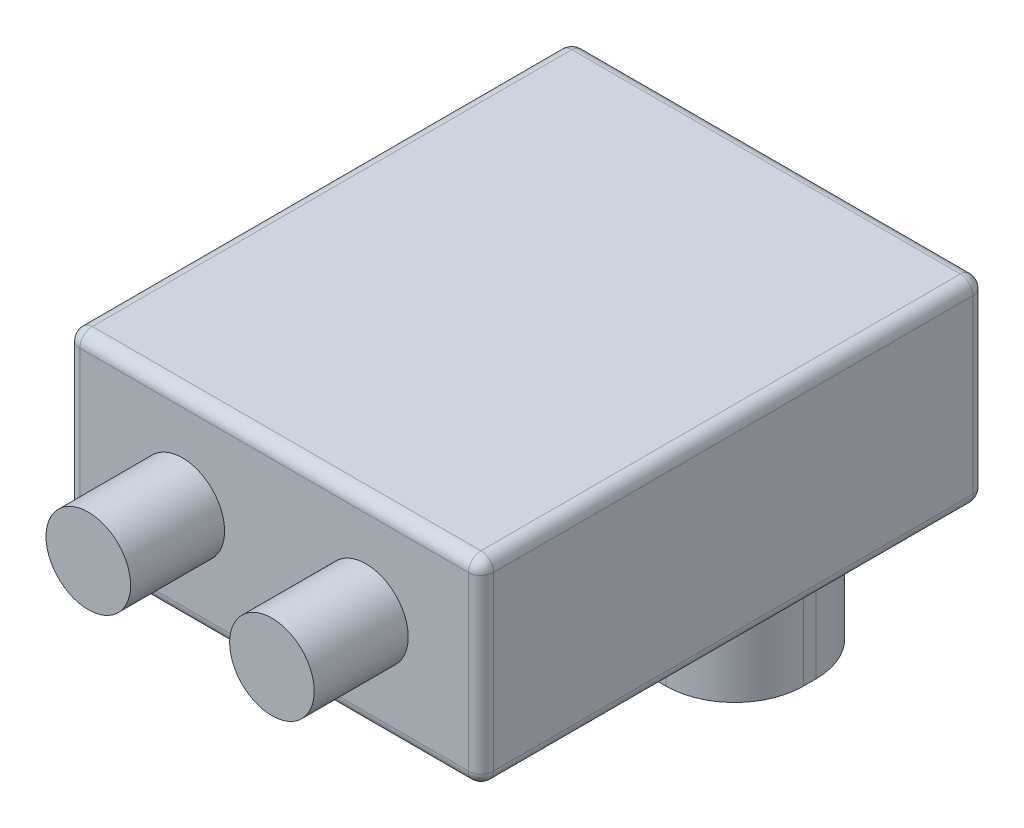
SolidWorks part; units mm, degrees
material "ABS"
ref_plane "X-Y Datum" through (0, 0, 0) normal (0, 0, 1) x (1, 0, 0)
ref_plane "X-Z Datum" through (0, 0, 0) normal (0, 1, 0) x (1, 0, 0)
ref_plane "Y-Z Datum" through (0, 0, 0) normal (1, 0, 0) x (0, 0, -1)
sketch "Sketch1" plane through (0, 0, 0) normal (0, 1, 0) x (1, 0, 0)
  line L1 (-33, 40.25) -> (33, 40.25)
  line L2 (-33, 40.25) -> (-33, -40.25)
  line L3 (-33, -40.25) -> (33, -40.25)
  line L4 (33, 40.25) -> (33, -40.25)
  line L5 (-33, 40.25) -> (33, -40.25) construction
  line L6 (-33, -40.25) -> (33, 40.25) construction
  point P0 (0, 0)
  dimension "D1" = 66
  dimension "D2" = 80.5
extrude "Boss-Extrude1" add sketch "Sketch1" along normal blind 24.14
sketch "Sketch2" plane through (0, 0, 0) normal (0, -1, 0) x (1, 0, 0)
  line L0 (25, -20.25) -> (-25, -20.25) construction
  line L6 (-25, -8.25) -> (25, -8.25)
  line L7 (-25, -8.25) -> (-25, -32.25)
  line L8 (-25, -32.25) -> (25, -32.25)
  line L9 (25, -8.25) -> (25, -32.25)
  line L11 (-33, 40.25) -> (33, 40.25) construction
  point P4 (0, -20.25)
  dimension "D1" = 72.5
  dimension "D2" = 24
  dimension "D3" = 50
extrude "Boss-Extrude2" add sketch "Sketch2" along normal blind 19
sketch "Sketch3" plane through (0, 24.14, 0) normal (0, 1, 0) x (1, 0, 0)
  line L4 (33, -40.25) -> (33, 40.25)
  line L5 (33, 40.25) -> (-33, 40.25)
  line L6 (-33, 40.25) -> (-33, -40.25)
  line L7 (-33, -40.25) -> (33, -40.25)
  line L8 (33, -40.25) -> (33, 40.25)
  line L9 (33, 40.25) -> (-33, 40.25)
  line L10 (-33, 40.25) -> (-33, -40.25)
  line L11 (-33, -40.25) -> (33, -40.25)
  dimension "D1" = 0
extrude "Boss-Extrude3" add sketch "Sketch3" along normal blind 7.3
fillet "Fillet1" radius 2 12 edges at (0, 0, -40.25) (0, 0, 40.25) (-33, 15.72, -40.25) (-33, 15.72, 40.25) (-33, 0, 0) (33, 15.72, 40.25) (33, 15.72, -40.25) (33, 0, 0) (0, 31.44, -40.25) (0, 31.44, 40.25) (-33, 31.44, 0) (33, 31.44, 0)
fillet "Fillet2" radius 11 4 edges at (25, -9.5, -8.25) (25, -9.5, -32.25) (-25, -9.5, -32.25) (-25, -9.5, -8.25)
sketch "Sketch4" plane through (0, 0, 40.25) normal (0, 0, 1) x (1, 0, 0)
  line L0 (0, 0) -> (0, 29.44) construction
  line L1 (31, 29.44) -> (-31, 29.44) construction
  line L2 (-31, 2) -> (31, 2) construction
  circle A0 centre (-14.65, 15.72) radius 6.75
  circle A2 centre (14.65, 15.72) radius 6.75
  dimension "D1" = 13.5
  dimension "D2" = 13.72
  dimension "D3" = 14.65
extrude "Boss-Extrude4" add sketch "Sketch4" along normal blind 15
